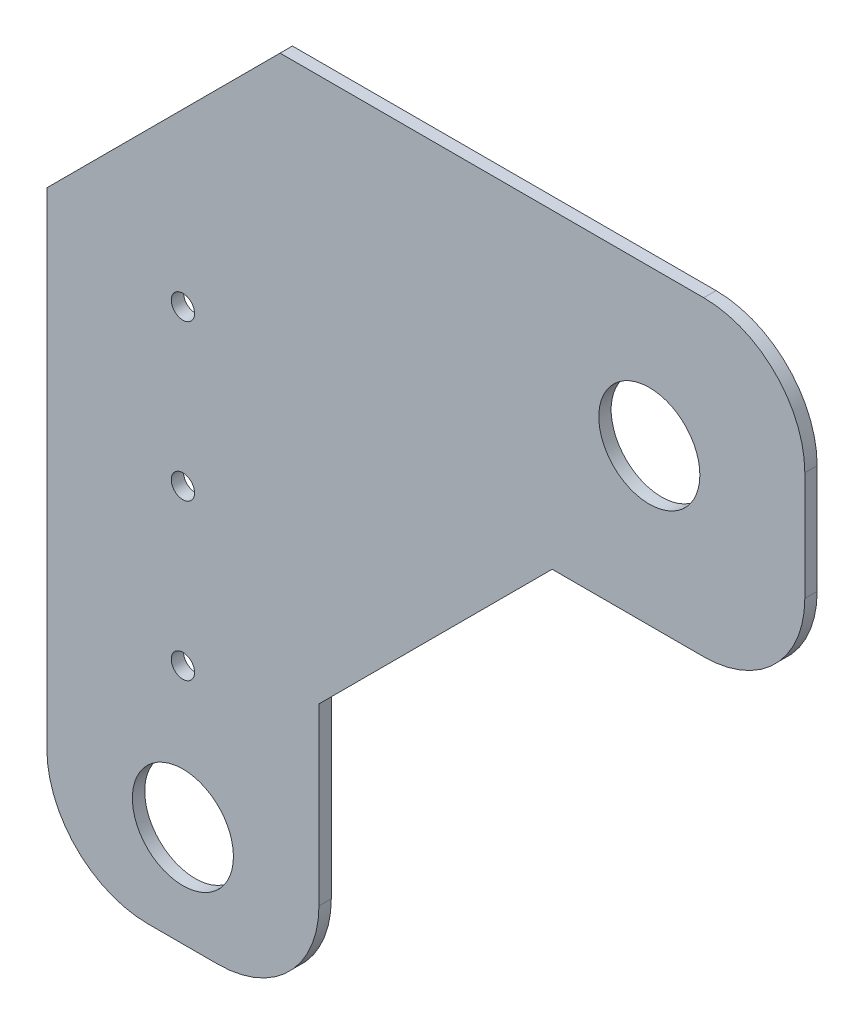
SolidWorks part; units mm, degrees
material "6061 Alloy"
ref_plane "Front Plane" through (0, 0, 0) normal (0, 0, 1) x (1, 0, 0)
ref_plane "Top Plane" through (0, 0, 0) normal (0, 1, 0) x (1, 0, 0)
ref_plane "Right Plane" through (0, 0, 0) normal (1, 0, 0) x (0, 0, -1)
sketch "Sketch1" plane through (0, 0, 0) normal (0, 0, 1) x (1, 0, 0)
  line L0 (0, 0) -> (0, 50)
  line L2 (35, 39.5) -> (35, 0)
  line L6 (0, 0) -> (35, 0) construction
  line L7 (5, 50) -> (5, 0) construction
  line L8 (0, 0) -> (5, 0) construction
  line L9 (5, 45) -> (5, 50) construction
  line L10 (17.5, 50) -> (17.5, -13) construction
  line L11 (0, 0) -> (0, -26)
  line L12 (0, -26) -> (35, -26)
  line L13 (0, 25) -> (5, 25) construction
  line L14 (35, -26) -> (35, 0)
  line L15 (17.5, -13) -> (17.5, 5) construction
  line L16 (17.5, 5) -> (30, 5) construction
  line L17 (77.5, 59.5) -> (17.5, 59.5) construction
  line L18 (17.5, 59.5) -> (17.5, 50) construction
  line L19 (0, 50) -> (0, 79.5)
  line L20 (0, 79.5) -> (97.5, 79.5)
  line L21 (97.5, 79.5) -> (97.5, 39.5)
  line L22 (97.5, 39.5) -> (35, 39.5)
  line L23 (77.5, 59.5) -> (77.5, 39.5) construction
  line L24 (77.5, 59.5) -> (77.5, 79.5) construction
  line L25 (77.5, 59.5) -> (97.5, 59.5) construction
  line L26 (35, 39.5) -> (35, 50) construction
  line L27 (35, 50) -> (17.5, 50) construction
  line L28 (17.5, 50) -> (5, 50) construction
  line L29 (5, 50) -> (0, 50) construction
  line L30 (5, 45) -> (30, 45) construction
  line L31 (5, 25) -> (30, 25) construction
  line L32 (5, 5) -> (30, 5) construction
  circle A0 centre (17.5, -13) radius 6.5
  circle A1 centre (5, 45) radius 1.5 construction
  circle A2 centre (5, 25) radius 1.5 construction
  circle A3 centre (5, 5) radius 1.5 construction
  circle A4 centre (30, 5) radius 1.5 construction
  circle A5 centre (30, 25) radius 1.5 construction
  circle A6 centre (30, 45) radius 1.5 construction
  circle A7 centre (77.5, 59.5) radius 6.5
  circle A8 centre (17.5, 45) radius 1.5
  circle A9 centre (17.5, 25) radius 1.5
  circle A10 centre (17.5, 5) radius 1.5
  point P41 (17.5, 45)
  dimension "D5" = 13
  dimension "D7" = 3
  dimension "D9" = 20
  dimension "D10" = 20
  dimension "D11" = 72.5
  dimension "D2" = 50
  dimension "D3" = 13
  dimension "D4" = 13
  dimension "D6" = 5
  dimension "D8" = 5
  dimension "D12" = 60
  dimension "D13" = 20
  dimension "D14" = 5
  dimension "D15" = 35
extrude "Boss-Extrude1" add sketch "Sketch1" along normal blind 1.5875
fillet "Fillet1" [suppressed] radius 5
fillet "Fillet2" radius 13 4 edges at (35, -26, 0.7937) (0, -26, 0.7937) (97.5, 39.5, 0.7937) (97.5, 79.5, 0.7937)
chamfer "Chamfer1" distance 30 angle 45 2 edges at (0, 79.5, 0.7937) (35, 39.5, 0.7937)
